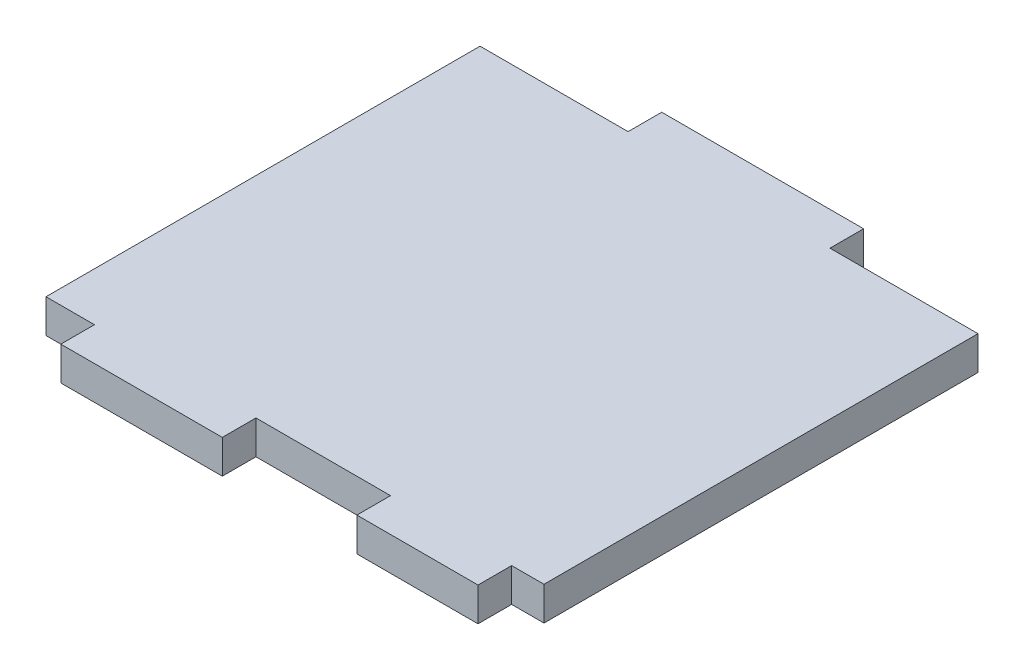
SolidWorks part; units mm, degrees
ref_plane "Front Plane" through (0, 0, 0) normal (0, 0, 1) x (1, 0, 0)
ref_plane "Top Plane" through (0, 0, 0) normal (0, 1, 0) x (1, 0, 0)
ref_plane "Right Plane" through (0, 0, 0) normal (1, 0, 0) x (0, 0, -1)
sketch "Sketch2" plane through (0, 0, 0) normal (0, 1, 0) x (1, 0, 0)
  line L0 (0, 0) -> (4.572, 0)
  line L1 (4.572, 0) -> (4.572, -3.175)
  line L2 (4.572, -3.175) -> (19.812, -3.175)
  line L3 (19.812, -3.175) -> (19.812, 0)
  line L4 (19.812, 0) -> (32.512, 0)
  line L5 (32.512, 0) -> (32.512, -3.175)
  line L6 (32.512, -3.175) -> (43.942, -3.175)
  line L7 (43.942, -3.175) -> (43.942, 0)
  line L8 (43.942, 0) -> (46.993, 0)
  line L9 (46.993, 0) -> (46.993, 40.9575)
  line L10 (46.993, 40.9575) -> (33.0215, 40.9575)
  line L11 (33.0215, 40.9575) -> (33.0215, 44.1325)
  line L12 (33.0215, 44.1325) -> (13.9715, 44.1325)
  line L13 (13.9715, 44.1325) -> (13.9715, 40.9575)
  line L14 (13.9715, 40.9575) -> (0, 40.9575)
  line L15 (0, 40.9575) -> (0, 0)
  dimension "D1" = 19.05
  dimension "D2" = 40.9575
  dimension "D3" = 3.175
  dimension "D4" = 11.43
  dimension "D5" = 15.24
  dimension "D6" = 12.7
  dimension "D7" = 4.572
  dimension "D8" = 3.051
extrude "Boss-Extrude1" add sketch "Sketch2" along normal blind 3.175
